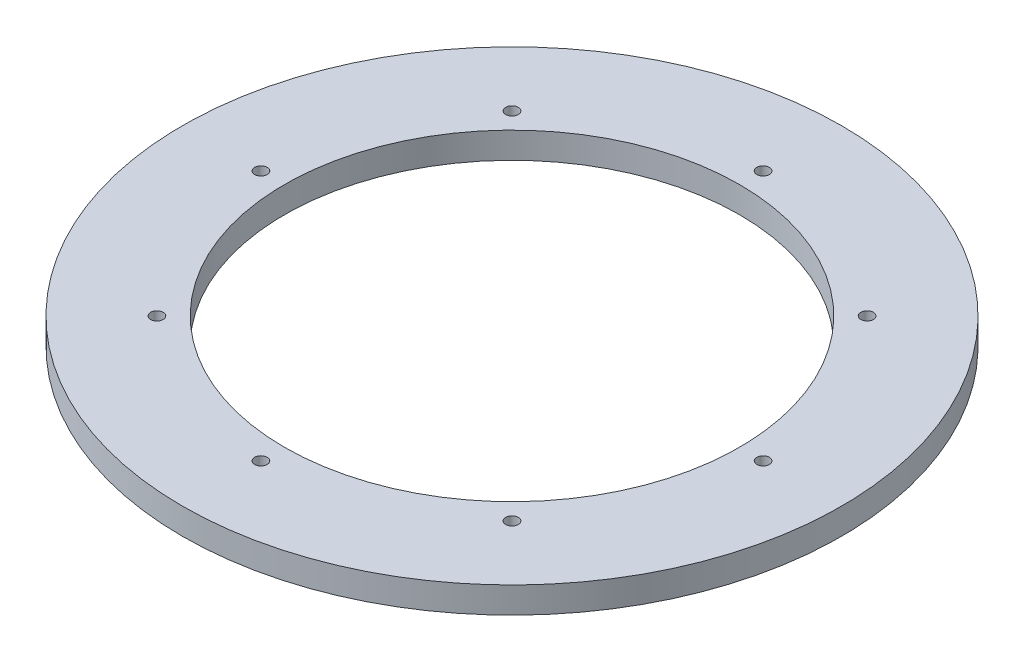
SolidWorks part; units mm, degrees
material "Custom Plastic"
ref_plane "Front Plane" through (0, 0, 0) normal (0, 0, 1) x (1, 0, 0)
ref_plane "Top Plane" through (0, 0, 0) normal (0, 1, 0) x (1, 0, 0)
ref_plane "Right Plane" through (0, 0, 0) normal (1, 0, 0) x (0, 0, -1)
sketch "Sketch1" plane through (0, 0, 0) normal (0, 1, 0) x (1, 0, 0)
  line L0 (0, -7310.1215) -> (0, 358195.9516) construction
  line L1 (-7310.1215, 0) -> (358195.9516, 0) construction
  circle A0 centre (0, 0) radius 315
  circle A1 centre (0, 0) radius 217.5
  circle A2 centre (0, 240) radius 6
  circle A3 centre (169.7056, 169.7056) radius 6
  circle A4 centre (240, 0) radius 6
  circle A5 centre (169.7056, -169.7056) radius 6
  circle A6 centre (0, -240) radius 6
  circle A7 centre (-169.7056, -169.7056) radius 6
  circle A8 centre (-240, 0) radius 6
  circle A9 centre (-169.7056, 169.7056) radius 6
  point P27 (0, 0)
  dimension "D1" = 630
  dimension "D2" = 435
  dimension "D4" = 12
  dimension "D3" = 240
  dimension "D5" = 8
extrude "Boss-Extrude1" add sketch "Sketch1" along normal mid plane 25
sketch "Sketch2" plane through (0, -12.5, 0) normal (0, -1, 0) x (1, 0, 0)
  circle A0 centre (0, 0) radius 255
  circle A1 centre (0, 0) radius 286
  dimension "D1" = 510
  dimension "D2" = 572
extrude "Cut-Extrude1" cut sketch "Sketch2" against normal blind 12
